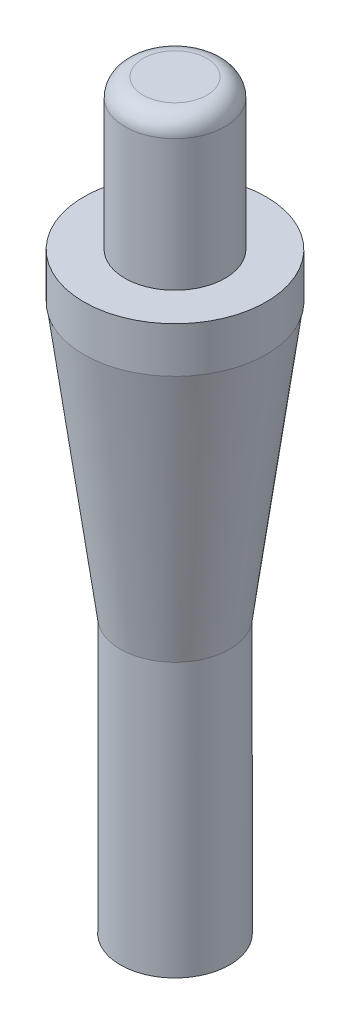
SolidWorks part; units mm, degrees
ref_plane "Front Plane" through (0, 0, 0) normal (0, 0, 1) x (1, 0, 0)
ref_plane "Top Plane" through (0, 0, 0) normal (0, 1, 0) x (1, 0, 0)
ref_plane "Right Plane" through (0, 0, 0) normal (1, 0, 0) x (0, 0, -1)
sketch "Sketch1" plane through (0, 0, 0) normal (1, 0, 0) x (0, 0, -1)
  line L0 (0, 26.5714) -> (0, -15.3974) construction
  line L1 (-2.75, 25.7) -> (-2.75, 17.5)
  line L2 (-2.75, 17.5) -> (-5, 17.5)
  line L3 (-5, 17.5) -> (-5, 15)
  line L4 (-5, 15) -> (-3, 15)
  line L5 (-3, 15) -> (-3, -15)
  line L6 (-3, -15) -> (-1.6, -15)
  line L7 (-1.6, -15) -> (-1.6, 10)
  line L8 (-1.6, 10) -> (0, 10)
  line L9 (-2.75, 25.7) -> (0, 25.7)
  line L10 (0, 10) -> (0, 25.7)
  point P16 (-3, 0)
  dimension "D1" = 3.2
  dimension "D2" = 6
  dimension "D3" = 30
  dimension "D4" = 2.5
  dimension "D5" = 10
  dimension "D6" = 5.5
  dimension "D7" = 8.2
  dimension "D8" = 25
revolve "Revolve1" add sketch "Sketch1" angle 360 about L0
fillet "Fillet1" radius 1 1 edges at (0, 25.7, 2.75)
chamfer "Chamfer1" distance 15 angle 7.5 1 edges at (0, 15, 3)
